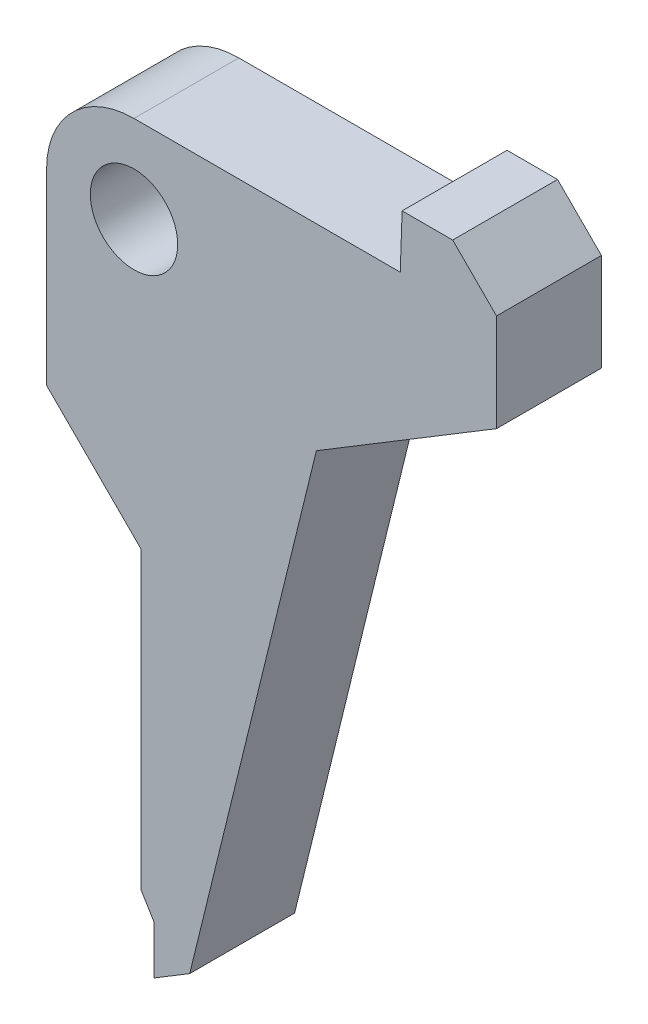
SolidWorks part; units mm, degrees
ref_plane "정면" through (0, 0, 0) normal (0, 0, 1) x (1, 0, 0)
ref_plane "윗면" through (0, 0, 0) normal (0, 1, 0) x (1, 0, 0)
ref_plane "우측면" through (0, 0, 0) normal (1, 0, 0) x (0, 0, -1)
sketch "스케치1" plane through (0, 0, 0) normal (0, 0, 1) x (1, 0, 0)
  line L0 (0, 5) -> (15.2324, 5)
  line L1 (15.2324, 5) -> (15.3404, 8.0924)
  line L2 (15.3404, 8.0924) -> (18.232, 8.0924)
  line L3 (18.232, 8.0924) -> (20.7411, 5.5833)
  line L4 (20.7411, 5.5833) -> (20.7411, 0)
  line L5 (20.7411, 0) -> (10.4355, -6.2443)
  line L6 (10.4355, -6.2443) -> (3.1885, -35.7764)
  line L7 (3.1885, -35.7764) -> (1.1404, -37.0174)
  line L8 (1.1404, -37.0174) -> (1.1404, -34.2332)
  line L9 (1.1404, -34.2332) -> (0.3893, -32.9935)
  line L10 (0.3893, -32.9935) -> (0.3893, -16.1179)
  line L11 (0.3893, -16.1179) -> (-5, -10.7286)
  line L12 (-5, 0) -> (-5, -10.7286)
  circle A0 centre (0, 0) radius 2.5
  circle A1 centre (0, 0) radius 5
  dimension "D1" = 5
  dimension "D2" = 10
  dimension "D3" = 92
extrude "보스-돌출1" add sketch "스케치1" along normal blind 6 contours A1 A0 | A1 L12 L11 L10 L9 L8 L7 L6 L5 L4 L3 L2 L1 L0
